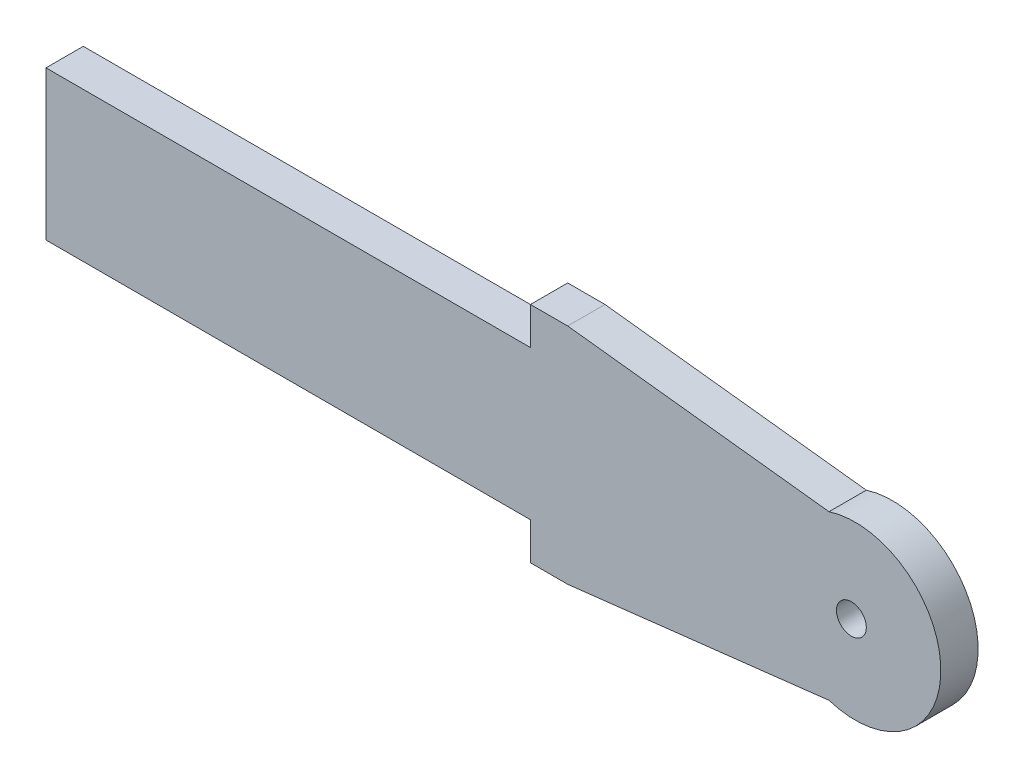
SolidWorks part; units mm, degrees
ref_plane "前视基准面" through (0, 0, 0) normal (0, 0, 1) x (1, 0, 0)
ref_plane "上视基准面" through (0, 0, 0) normal (0, 1, 0) x (1, 0, 0)
ref_plane "右视基准面" through (0, 0, 0) normal (1, 0, 0) x (0, 0, -1)
other "Configuration Table"
sketch "草图1" plane through (0, 0, 0) normal (0, 0, 1) x (1, 0, 0)
  line L0 (0, 0) -> (50000, 0) construction
  line L1 (0, 0) -> (0, 50000) construction
  line L3 (-120, 30) -> (120, 30)
  line L4 (-120, 30) -> (-120, -30)
  line L5 (-120, -30) -> (120, -30)
  line L6 (120, 30) -> (120, -30)
extrude "凸台-拉伸1" add sketch "草图1" along normal blind 10
sketch "草图2" plane through (0, 0, 10) normal (0, 0, 1) x (1, 0, 0)
  line L0 (0, 0) -> (50000, 0) construction
  line L1 (0, 0) -> (0, 50000) construction
  line L2 (-120, 30) -> (-120, -30) construction
  line L3 (-120, 20) -> (9.92, 20)
  line L4 (-120, 20) -> (-120, -20)
  line L5 (-120, -20) -> (9.92, -20)
  line L6 (9.92, 20) -> (9.92, -20)
  line L7 (120, 30) -> (-120, 30) construction
  line L8 (9.92, -30) -> (19.92, -30)
  line L9 (9.92, 20) -> (19.92, 20)
  line L10 (9.92, 20) -> (9.92, 30)
  line L11 (9.92, 30) -> (19.92, 30)
  line L12 (19.92, 20) -> (19.92, 30)
  line L13 (19.92, -20) -> (19.92, -30)
  line L14 (9.92, -20) -> (19.92, -20)
  line L15 (9.92, -20) -> (9.92, -30)
  line L16 (90, 69.9647) -> (90, -54.9409)
  line L17 (19.92, 30) -> (90, 21.9089)
  line L18 (120, 0) -> (120, 50000) construction
  line L19 (120, -30) -> (120, 30) construction
  line L20 (19.92, -30) -> (90, -21.9089)
  line L21 (19.92, 30) -> (120, 30)
  line L22 (120, 30) -> (120, -30)
  line L23 (120, -30) -> (19.92, -30)
  circle A0 centre (97, 0) radius 23
  point P25 (120, 0)
  line M10 (-120, 30) -> (-120, -30)
  line M11 (-120, -30) -> (120, -30)
  line M12 (120, -30) -> (120, 30)
  line M13 (120, 30) -> (-120, 30)
  dimension "D2" = 23
  dimension "D1" = 10
  dimension "D3" = 30
extrude "切除-拉伸2" cut sketch "草图2" against normal blind 10 contours L17 L16 M13 | A0 L22 L16 M13 | A0 L16 M11 M12 | L20 L16 M11 | L3 L10 M13 M10 | L15 L5 M10 M11
sketch "草图3" plane through (0, 0, 10) normal (0, 0, 1) x (1, 0, 0)
  line L0 (0, 0) -> (50000, 0) construction
  line L1 (0, 0) -> (0, 50000) construction
  line L2 (120, 0) -> (120, 22.2319)
  circle A0 centre (96, 0) radius 4
  arc A1 (90, -21.9089) -> (90, 21.9089) centre (97, 0) ccw construction
  dimension "D1" = 24
extrude "切除-拉伸3" cut sketch "草图3" against normal blind 10 contours A0
